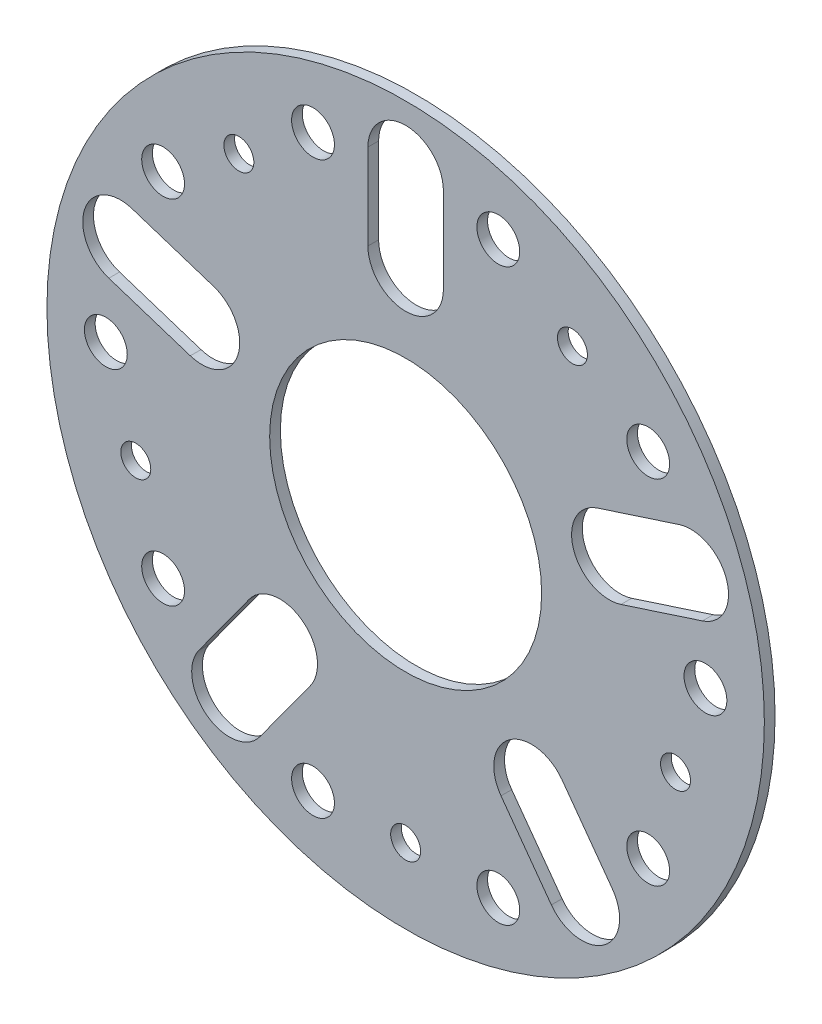
SolidWorks part; units mm, degrees
ref_plane "前视基准面" through (0, 0, 0) normal (0, 0, 1) x (1, 0, 0)
ref_plane "上视基准面" through (0, 0, 0) normal (0, 1, 0) x (1, 0, 0)
ref_plane "右视基准面" through (0, 0, 0) normal (1, 0, 0) x (0, 0, -1)
sketch "草图1" plane through (0, 0, 0) normal (0, 0, 1) x (1, 0, 0)
  line L0 (-25.203, -8.189) -> (0, -26.5) construction
  line L1 (0, 0) -> (-12.6015, -17.3445) construction
  line L2 (-12.6015, -17.3445) -> (-22.2404, -30.6113) construction
  line L3 (0, 0) -> (0, -44.5087) construction
  line L4 (0, 0) -> (-14.8252, -45.6273) construction
  line L5 (-16.458, -22.6525) -> (-11.7557, -16.1803) construction
  line L8 (-19.3088, -20.5812) -> (-14.6065, -14.1091)
  line L11 (-13.6072, -24.7237) -> (-8.9049, -18.2516)
  line L14 (-26.6296, 8.6525) -> (-19.0211, 6.1803) construction
  line L17 (-25.5407, 12.0038) -> (-17.9322, 9.5317)
  line L20 (-27.7185, 5.3011) -> (-20.1101, 2.829)
  line L21 (0, 28) -> (0, 20) construction
  line L22 (3.5238, 28) -> (3.5238, 20)
  line L23 (-3.5238, 28) -> (-3.5238, 20)
  line L24 (26.6296, 8.6525) -> (19.0211, 6.1803) construction
  line L25 (27.7185, 5.3011) -> (20.1101, 2.829)
  line L26 (25.5407, 12.0038) -> (17.9322, 9.5317)
  line L27 (16.458, -22.6525) -> (11.7557, -16.1803) construction
  line L28 (13.6072, -24.7237) -> (8.9049, -18.2516)
  line L29 (19.3088, -20.5812) -> (14.6065, -14.1091)
  circle A0 centre (0, 0) radius 12.7
  circle A1 centre (0, 0) radius 26.5 construction
  circle A2 centre (0, 0) radius 28 construction
  circle A3 centre (0, -26.5) radius 1.4
  circle A4 centre (-25.203, -8.189) radius 1.4
  circle A5 centre (-15.5763, 21.439) radius 1.4
  circle A6 centre (15.5763, 21.439) radius 1.4
  circle A7 centre (25.203, -8.189) radius 1.4
  circle A8 centre (-8.6518, -26.6274) radius 2
  circle A13 centre (-16.458, -22.6525) radius 2 construction
  circle A14 centre (8.6518, -26.6274) radius 2
  circle A15 centre (-27.9977, 0) radius 2
  circle A16 centre (-22.6506, -16.4567) radius 2
  circle A17 centre (-8.6518, 26.6274) radius 2
  circle A18 centre (-22.6506, 16.4567) radius 2
  circle A19 centre (22.6506, 16.4567) radius 2
  circle A20 centre (8.6518, 26.6274) radius 2
  circle A21 centre (22.6506, -16.4567) radius 2
  circle A22 centre (27.9977, 0) radius 2
  circle A23 centre (0, 0) radius 33.5
  circle A34 centre (0, 0) radius 20 construction
  arc A35 (-19.3088, -20.5812) -> (-13.6072, -24.7237) centre (-16.458, -22.6525) ccw
  arc A36 (-8.9049, -18.2516) -> (-14.6065, -14.1091) centre (-11.7557, -16.1803) ccw
  arc A37 (-25.5407, 12.0038) -> (-27.7185, 5.3011) centre (-26.6296, 8.6525) ccw
  arc A38 (-20.1101, 2.829) -> (-17.9322, 9.5317) centre (-19.0211, 6.1803) ccw
  arc A39 (3.5238, 28) -> (-3.5238, 28) centre (0, 28) ccw
  arc A40 (-3.5238, 20) -> (3.5238, 20) centre (0, 20) ccw
  arc A41 (27.7185, 5.3011) -> (25.5407, 12.0038) centre (26.6296, 8.6525) ccw
  arc A42 (17.9322, 9.5317) -> (20.1101, 2.829) centre (19.0211, 6.1803) ccw
  arc A43 (13.6072, -24.7237) -> (19.3088, -20.5812) centre (16.458, -22.6525) ccw
  arc A44 (14.6065, -14.1091) -> (8.9049, -18.2516) centre (11.7557, -16.1803) ccw
  point P27 (-14.1068, -19.4164)
  point P53 (-22.8254, 7.4164)
  point P60 (0, 24)
  point P67 (22.8254, 7.4164)
  point P74 (14.1068, -19.4164)
  dimension "D1" = 25.4
  dimension "D2" = 53
  dimension "D3" = 56
  dimension "D4" = 2.8
  dimension "D7" = 4
  dimension "D9" = 67
  dimension "D10" = 40
  dimension "D6" = 18
  dimension "D5" = 5
  dimension "D8" = 5
  dimension "D11" = 5
extrude "凸台-拉伸1" add sketch "草图1" along normal blind 1 contours A23
